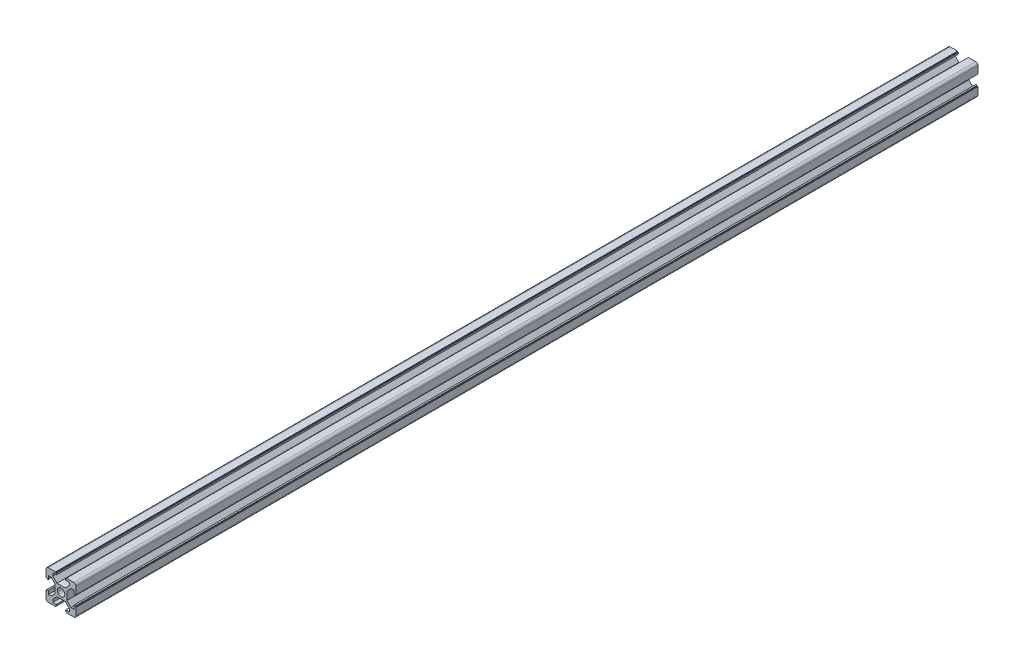
SolidWorks part; units mm, degrees
ref_plane "前视基准面" through (0, 0, 0) normal (0, 0, 1) x (1, 0, 0)
ref_plane "上视基准面" through (0, 0, 0) normal (0, 1, 0) x (1, 0, 0)
ref_plane "右视基准面" through (0, 0, 0) normal (1, 0, 0) x (0, 0, -1)
other "Configuration Table"
sketch "草图1" plane through (0, 0, 0) normal (1, 0, 0) x (0, 0, -1)
  line L0 (0, 0) -> (600, 0)
  dimension "D1" = 600
other "铝型材 20 X 20 X R1.5(1)"
ref_plane "基准面1" through (0, 0, 0) normal (0, 0, -1) x (0, 1, 0)
sketch "Sketch1" plane through (0, 0, 0) normal (0, 0, -1) x (0, 1, 0)
  line L0 (-3.6, 10) -> (-3.6, 9.5)
  line L1 (-3.6, 9.5) -> (-3.1, 9.5)
  line L2 (-3.1, 9.5) -> (-3.1, 8.5)
  line L3 (-3.1, 8.5) -> (-5.5, 8.5)
  line L4 (-8.5, -10) -> (-3.6, -10)
  line L5 (-10, -8.5) -> (-10, -3.6)
  line L6 (8.5, 10) -> (3.6, 10)
  line L7 (10, 8.5) -> (10, 3.6)
  line L8 (0, 14.8756) -> (0, 0) construction
  line L9 (0, 0) -> (14.1675, 0) construction
  line L10 (-5.5, 8.5) -> (-5.5, 6.65)
  line L11 (-5.5, 6.65) -> (-2.75, 3.9)
  line L12 (-2.75, 3.9) -> (2.75, 3.9)
  line L13 (5.5, 6.65) -> (2.75, 3.9)
  line L14 (5.5, 8.5) -> (5.5, 6.65)
  line L15 (3.1, 8.5) -> (5.5, 8.5)
  line L16 (3.1, 9.5) -> (3.1, 8.5)
  line L17 (3.6, 9.5) -> (3.1, 9.5)
  line L18 (3.6, 10) -> (3.6, 9.5)
  line L19 (-3.6, 10) -> (-8.5, 10)
  line L20 (10, 3.6) -> (9.5, 3.6)
  line L21 (9.5, 3.6) -> (9.5, 3.1)
  line L22 (9.5, 3.1) -> (8.5, 3.1)
  line L23 (8.5, 3.1) -> (8.5, 5.5)
  line L24 (8.5, 5.5) -> (6.65, 5.5)
  line L25 (6.65, 5.5) -> (3.9, 2.75)
  line L26 (3.9, 2.75) -> (3.9, -2.75)
  line L27 (6.65, -5.5) -> (3.9, -2.75)
  line L28 (8.5, -5.5) -> (6.65, -5.5)
  line L29 (8.5, -3.1) -> (8.5, -5.5)
  line L30 (9.5, -3.1) -> (8.5, -3.1)
  line L31 (9.5, -3.6) -> (9.5, -3.1)
  line L32 (10, -3.6) -> (9.5, -3.6)
  line L33 (3.6, -10) -> (3.6, -9.5)
  line L34 (3.6, -9.5) -> (3.1, -9.5)
  line L35 (3.1, -9.5) -> (3.1, -8.5)
  line L36 (3.1, -8.5) -> (5.5, -8.5)
  line L37 (5.5, -8.5) -> (5.5, -6.65)
  line L38 (5.5, -6.65) -> (2.75, -3.9)
  line L39 (2.75, -3.9) -> (-2.75, -3.9)
  line L40 (-5.5, -6.65) -> (-2.75, -3.9)
  line L41 (-5.5, -8.5) -> (-5.5, -6.65)
  line L42 (-3.1, -8.5) -> (-5.5, -8.5)
  line L43 (-3.1, -9.5) -> (-3.1, -8.5)
  line L44 (-3.6, -9.5) -> (-3.1, -9.5)
  line L45 (-3.6, -10) -> (-3.6, -9.5)
  line L46 (-10, -3.6) -> (-9.5, -3.6)
  line L47 (-9.5, -3.6) -> (-9.5, -3.1)
  line L48 (-9.5, -3.1) -> (-8.5, -3.1)
  line L49 (-8.5, -3.1) -> (-8.5, -5.5)
  line L50 (-8.5, -5.5) -> (-6.65, -5.5)
  line L51 (-6.65, -5.5) -> (-3.9, -2.75)
  line L52 (-3.9, -2.75) -> (-3.9, 2.75)
  line L53 (-6.65, 5.5) -> (-3.9, 2.75)
  line L54 (-8.5, 5.5) -> (-6.65, 5.5)
  line L55 (-8.5, 3.1) -> (-8.5, 5.5)
  line L56 (-9.5, 3.1) -> (-8.5, 3.1)
  line L57 (-9.5, 3.6) -> (-9.5, 3.1)
  line L58 (-10, 3.6) -> (-9.5, 3.6)
  line L59 (3.6, -10) -> (8.5, -10)
  line L60 (-10, 3.6) -> (-10, 8.5)
  line L61 (10, -3.6) -> (10, -8.5)
  circle A0 centre (0, 0) radius 2.5
  arc A1 (-10, 8.5) -> (-8.5, 10) centre (-8.5, 8.5) cw
  arc A2 (10, 8.5) -> (8.5, 10) centre (8.5, 8.5) ccw
  arc A3 (-8.5, -10) -> (-10, -8.5) centre (-8.5, -8.5) cw
  arc A4 (8.5, -10) -> (10, -8.5) centre (8.5, -8.5) ccw
  point P0 (-10, 0)
  point P1 (10, 0)
  point P2 (0, 10)
  point P3 (0, -10)
  point P4 (0, 0)
  point P5 (-10, -10)
  point P6 (10, -10)
  point P7 (10, 10)
  point P8 (-10, 10)
  point P13 (0, 0)
  point P36 (-10, 10)
  point P39 (10, 10)
  dimension "D1" = 11
  dimension "D2" = 20
  dimension "D3" = 6.2
  dimension "D4" = 7.2
  dimension "D5" = 6.1
  dimension "D6" = 5
  dimension "D7" = 1.5
  dimension "D8" = 45
  dimension "D9" = 0.5
  dimension "D10" = 1
  dimension "D11" = 5.5
